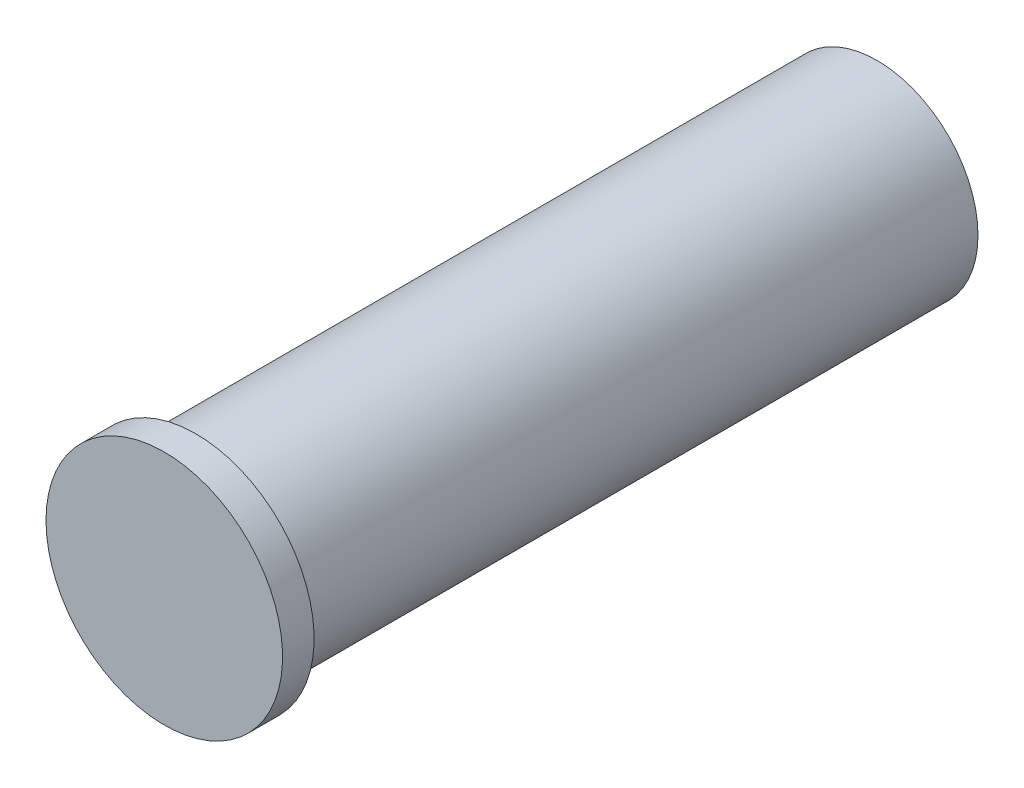
SolidWorks part; units mm, degrees
ref_plane "Front Plane" through (0, 0, 0) normal (0, 0, 1) x (1, 0, 0)
ref_plane "Top Plane" through (0, 0, 0) normal (0, 1, 0) x (1, 0, 0)
ref_plane "Right Plane" through (0, 0, 0) normal (1, 0, 0) x (0, 0, -1)
sketch "Sketch1" plane through (0, 0, 0) normal (0, 0, 1) x (1, 0, 0)
  circle A0 centre (0, 0) radius 3.048
  circle A1 centre (0, 0) radius 1.4605
  dimension "D1" = 6.096
  dimension "D2" = 1.5875
extrude "Boss-Extrude1" add sketch "Sketch1" along normal blind 20.574
sketch "Sketch2" plane through (0, 0, 20.574) normal (0, 0, 1) x (1, 0, 0)
  circle A0 centre (0, 0) radius 3.5719
  dimension "D1" = 7.1437
extrude "Boss-Extrude2" add sketch "Sketch2" along normal blind 0.9525
